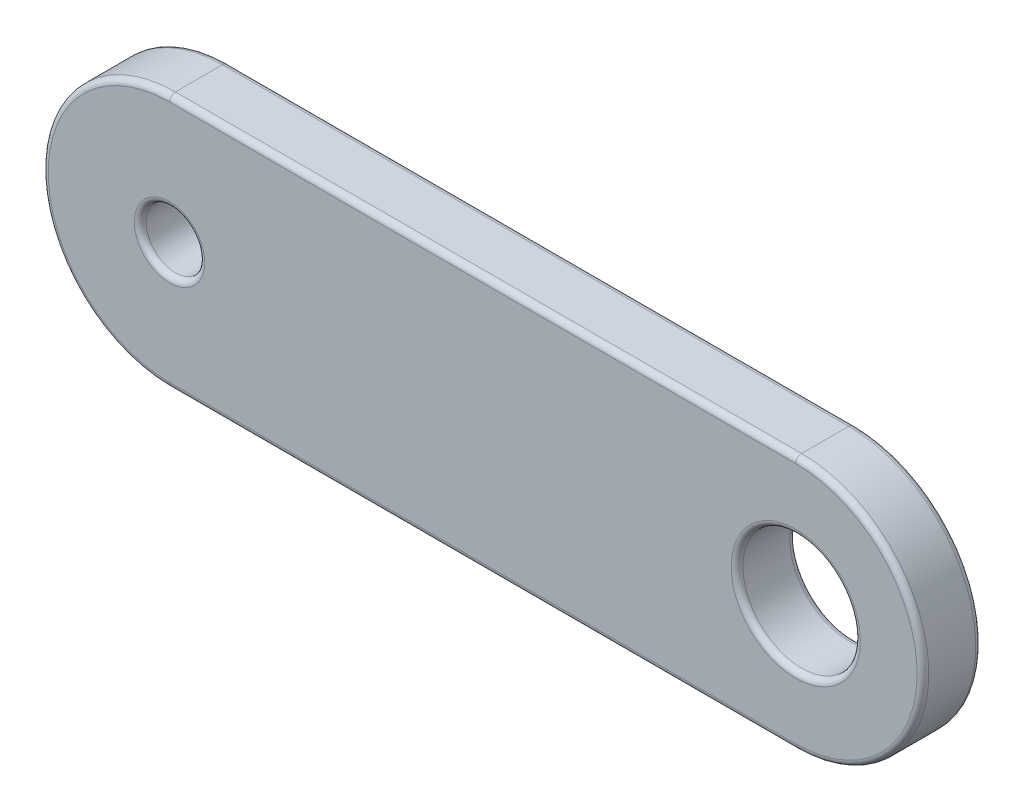
SolidWorks part; units mm, degrees
ref_plane "Front Plane" through (0, 0, 0) normal (0, 0, 1) x (1, 0, 0)
ref_plane "Top Plane" through (0, 0, 0) normal (0, 1, 0) x (1, 0, 0)
ref_plane "Right Plane" through (0, 0, 0) normal (1, 0, 0) x (0, 0, -1)
sketch "Sketch1" plane through (0, 0, 0) normal (0, 0, 1) x (1, 0, 0)
  line L0 (-8, 0) -> (8, 0) construction
  line L1 (-8, 3.25) -> (8, 3.25)
  line L2 (-8, -3.25) -> (8, -3.25)
  arc A0 (-8, 3.25) -> (-8, -3.25) centre (-8, 0) ccw
  arc A1 (8, -3.25) -> (8, 3.25) centre (8, 0) ccw
  circle A2 centre (-8, 0) radius 0.75
  circle A3 centre (8, 0) radius 1.5
  point P2 (0, 0)
  dimension "D3" = 1.5
  dimension "D4" = 3
  dimension "D1" = 16
  dimension "D2" = 6.5
extrude "Boss-Extrude1" add sketch "Sketch1" along normal mid plane 1.5
fillet "Fillet1" radius 0.15 12 edges at (9.5, 0, -0.75) (0, -3.25, -0.75) (11.25, 0, -0.75) (0, 3.25, -0.75) (-11.25, 0, -0.75) (-7.25, 0, -0.75) (9.5, 0, 0.75) (0, 3.25, 0.75) (11.25, 0, 0.75) (0, -3.25, 0.75) (-11.25, 0, 0.75) (-7.25, 0, 0.75)
